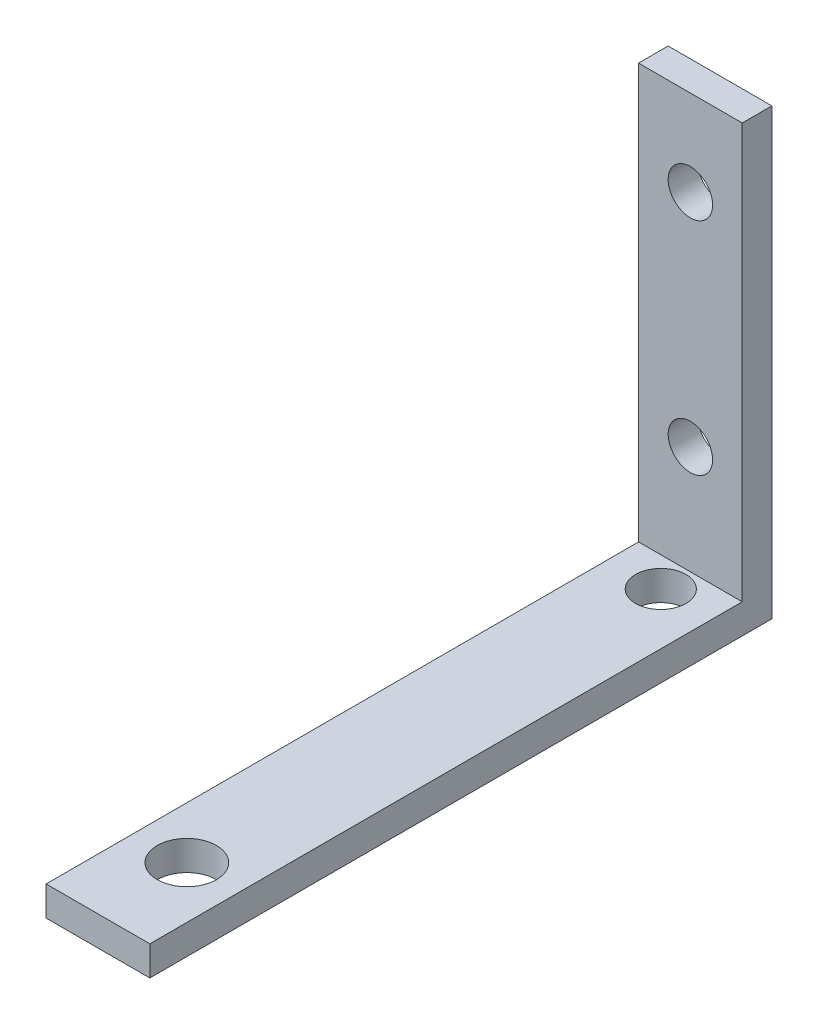
SolidWorks part; units mm, degrees
ref_plane "Plano frontal" through (0, 0, 0) normal (0, 0, 1) x (1, 0, 0)
ref_plane "Plano superior" through (0, 0, 0) normal (0, 1, 0) x (1, 0, 0)
ref_plane "Plano direito" through (0, 0, 0) normal (1, 0, 0) x (0, 0, -1)
sketch "Esboço2" plane through (0, 0, 0) normal (0, 0, 1) x (1, 0, 0)
  line L1 (-3.5, -15) -> (3.5, -15)
  line L2 (-3.5, -15) -> (-3.5, 15)
  line L3 (-3.5, 15) -> (3.5, 15)
  line L4 (3.5, -15) -> (3.5, 15)
  line L5 (-3.5, -15) -> (3.5, 15) construction
  line L6 (-3.5, 15) -> (3.5, -15) construction
  point P0 (0, 0)
  dimension "D1" = 30
  dimension "D2" = 7
extrude "Ressalto-extrusão1" add sketch "Esboço2" along normal blind 2
sketch "Esboço3" plane through (0, 0, 2) normal (0, 0, 1) x (1, 0, 0)
  line L0 (-3.5, 15) -> (-3.5, -15) construction
  line L1 (3.5, -15) -> (-3.5, -15)
  line L2 (3.5, -15) -> (3.5, -13)
  line L3 (3.5, -13) -> (-3.5, -13)
  line L4 (-3.5, -15) -> (-3.5, -13)
  dimension "D1" = 2
extrude "Ressalto-extrusão2" add sketch "Esboço3" along normal blind 40
sketch "Esboço4" plane through (0, -15, 0) normal (0, -1, 0) x (1, 0, 0)
  line L0 (0, 0) -> (0, 4) construction
  line L1 (-3.5, 0) -> (3.5, 0) construction
  line L2 (0, 4) -> (0, 36) construction
  circle A0 centre (0, 4) radius 1.7
  circle A1 centre (0, 36) radius 2
  dimension "D2" = 3.4
  dimension "D4" = 4
  dimension "D1" = 4
  dimension "D3" = 32
extrude "Corte-extrusão1" cut sketch "Esboço4" against normal up to next
sketch "Esboço5" plane through (0, 0, 2) normal (0, 0, 1) x (1, 0, 0)
  line L0 (0, 15) -> (0, -9.8763) construction
  line L1 (3.5, 15) -> (-3.5, 15) construction
  circle A0 centre (0, -5.6959) radius 1.5
  circle A1 centre (0, 9.1992) radius 1.5
  dimension "D1" = 3
  dimension "D2" = 3
extrude "Corte-extrusão2" cut sketch "Esboço5" against normal blind 10
